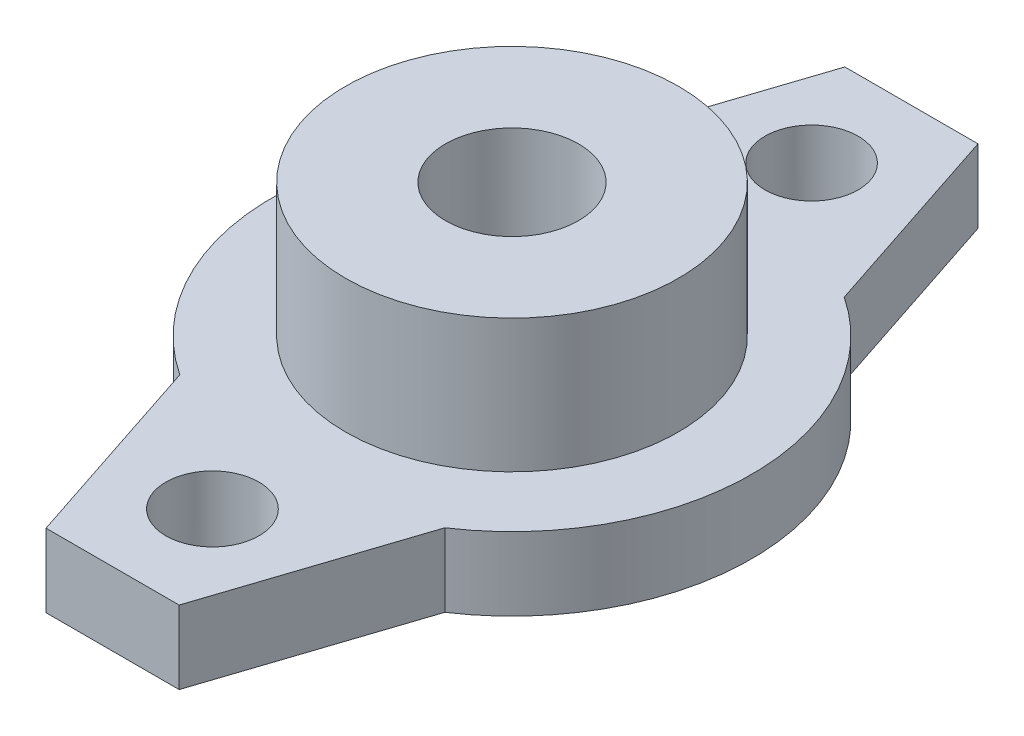
SolidWorks part; units mm, degrees
ref_plane "Plan de face" through (0, 0, 0) normal (0, 0, 1) x (1, 0, 0)
ref_plane "Plan de dessus" through (0, 0, 0) normal (0, 1, 0) x (1, 0, 0)
ref_plane "Plan de droite" through (0, 0, 0) normal (1, 0, 0) x (0, 0, -1)
sketch "Esquisse1" plane through (0, 0, 0) normal (0, 1, 0) x (1, 0, 0)
  line L0 (-9.9499, 15) -> (-5, 30)
  line L1 (-5, 30) -> (5, 30)
  line L2 (0, 30) -> (0, -30) construction
  line L3 (0, 0) -> (-18, 0) construction
  line L4 (0, -55) -> (0, 55) construction
  line L5 (9.9499, 15) -> (5, 30)
  line L6 (-55, 0) -> (55, 0) construction
  line L7 (9.9499, -15) -> (5, -30)
  line L8 (-5, -30) -> (5, -30)
  line L9 (-9.9499, -15) -> (-5, -30)
  arc A0 (-9.9499, -15) -> (-9.9499, 15) centre (0, 0) cw
  arc A1 (9.9499, -15) -> (9.9499, 15) centre (0, 0) ccw
  dimension "D2" = 30
  dimension "D3" = 5
  dimension "D4" = 15
extrude "Boss.-Extru.1" add sketch "Esquisse1" along normal blind 5.5
sketch "Esquisse2" plane through (0, 5.5, 0) normal (0, 1, 0) x (1, 0, 0)
  circle A0 centre (0, 0) radius 12.5
  circle A1 centre (0, 0) radius 5
  dimension "D1" = 25
  dimension "D2" = 10
extrude "Boss.-Extru.2" add sketch "Esquisse2" along normal blind 10
sketch "Esquisse3" plane through (0, 5.5, 0) normal (0, 1, 0) x (1, 0, 0)
  circle A0 centre (0, 0) radius 5 construction
  circle A1 centre (0, 0) radius 5
extrude "Enlèv. mat.-Extru.1" cut sketch "Esquisse3" against normal blind 10
sketch "Esquisse4" plane through (0, 5.5, 0) normal (0, 1, 0) x (1, 0, 0)
  circle A0 centre (0, 0) radius 22.5 construction
  circle A1 centre (0, 22.5) radius 3.5
  circle A2 centre (0, -22.5) radius 3.5
  dimension "D1" = 45
  dimension "D2" = 7
  dimension "D3" = 7
extrude "Enlèv. mat.-Extru.2" cut sketch "Esquisse4" against normal blind 10
hole_wizard "Dégagement M61" positions "Esquisse5" profile "Esquisse6" hole size "M6" standard "ISO"
sketch "Esquisse5" plane through (0, 0, 0) normal (0, 1, 0) x (0, 0, -1)
  point P0 (22.5, 0)
  point P3 (-22.5, 0)
sketch "Esquisse6" plane through (0, 0, -22.5) normal (1, 0, 0) x (0, 0, 1)
  line L0 (0, 0) -> (0, 122.103)
  line L1 (0, 122.103) -> (3.5, 120)
  line L2 (3.5, 120) -> (3.5, 0)
  line L3 (3.5, 0) -> (0, 0)
  line L4 (0, 122.103) -> (-3.5, 120) construction
  line L5 (0, -6.35) -> (0, 107.95) construction
  dimension "Diamètre du perçage" = 7
  dimension "Profondeur du perçage" = 120
  dimension "Angle de pointe" = 118
hole_wizard "Dégagement M62" positions "Esquisse7" profile "Esquisse8" hole size "M6" standard "ISO"
sketch "Esquisse7" plane through (0, -60, 0) normal (0, -1, 0) x (0, 0, 1)
  point P0 (22.5, 0)
  point P3 (-22.5, 0)
sketch "Esquisse8" plane through (0, -60, 22.5) normal (1, 0, 0) x (0, 0, -1)
  line L0 (0, 0) -> (0, 122.103)
  line L1 (0, 122.103) -> (3.5, 120)
  line L2 (3.5, 120) -> (3.5, 0)
  line L3 (3.5, 0) -> (0, 0)
  line L4 (0, 122.103) -> (-3.5, 120) construction
  line L5 (0, -6.35) -> (0, 107.95) construction
  dimension "Diamètre du perçage" = 7
  dimension "Profondeur du perçage" = 120
  dimension "Angle de pointe" = 118
